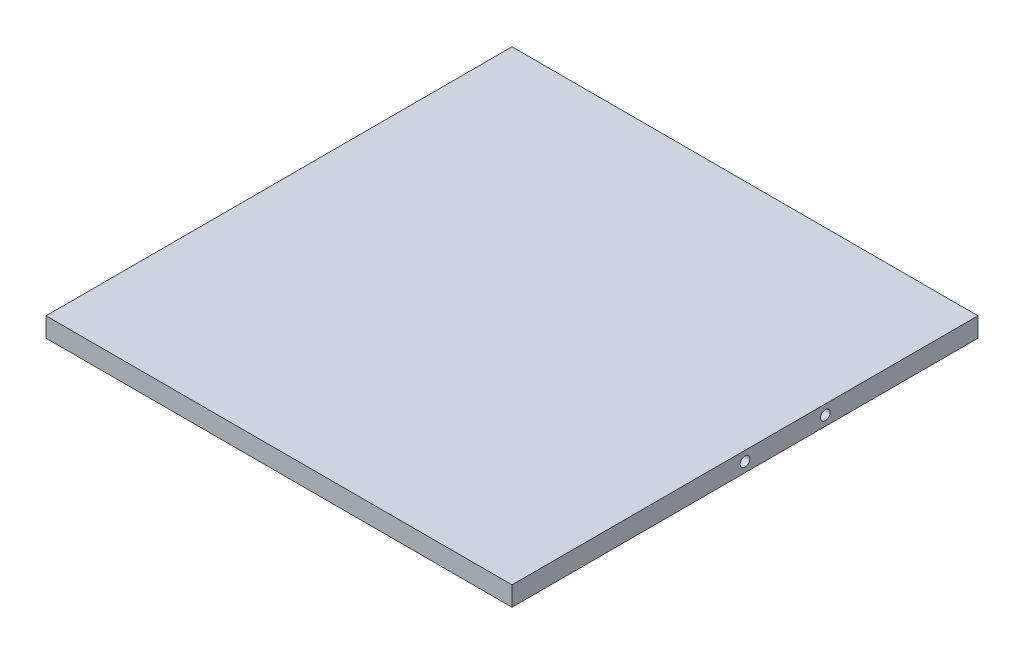
SolidWorks part; units mm, degrees
ref_plane "Front Plane" through (0, 0, 0) normal (0, 0, 1) x (1, 0, 0)
ref_plane "Top Plane" through (0, 0, 0) normal (0, 1, 0) x (1, 0, 0)
ref_plane "Right Plane" through (0, 0, 0) normal (1, 0, 0) x (0, 0, -1)
sketch "Sketch2" plane through (0, 0, 0) normal (0, 1, 0) x (1, 0, 0)
  line L1 (-250.8402, 154.9522) -> (53.9598, 154.9522)
  line L2 (-250.8402, 154.9522) -> (-250.8402, -149.8478)
  line L3 (-250.8402, -149.8478) -> (53.9598, -149.8478)
  line L4 (53.9598, 154.9522) -> (53.9598, -149.8478)
  dimension "D1" = 304.8
  dimension "D2" = 304.8
extrude "Boss-Extrude1" add sketch "Sketch2" along normal blind 12.7
sketch "Sketch3" plane through (53.9598, 0, 0) normal (1, 0, 0) x (0, 0, -1)
  circle A0 centre (2.5522, 6.35) radius 3.175
  dimension "D1" = 6.35
extrude "Cut-Extrude1" cut sketch "Sketch3" against normal through all
sketch "Sketch4" plane through (-250.8402, 0, 0) normal (-1, 0, 0) x (0, 0, 1)
  circle A0 centre (-55.109, 6.35) radius 3.175
extrude "Cut-Extrude2" cut sketch "Sketch4" against normal through all
